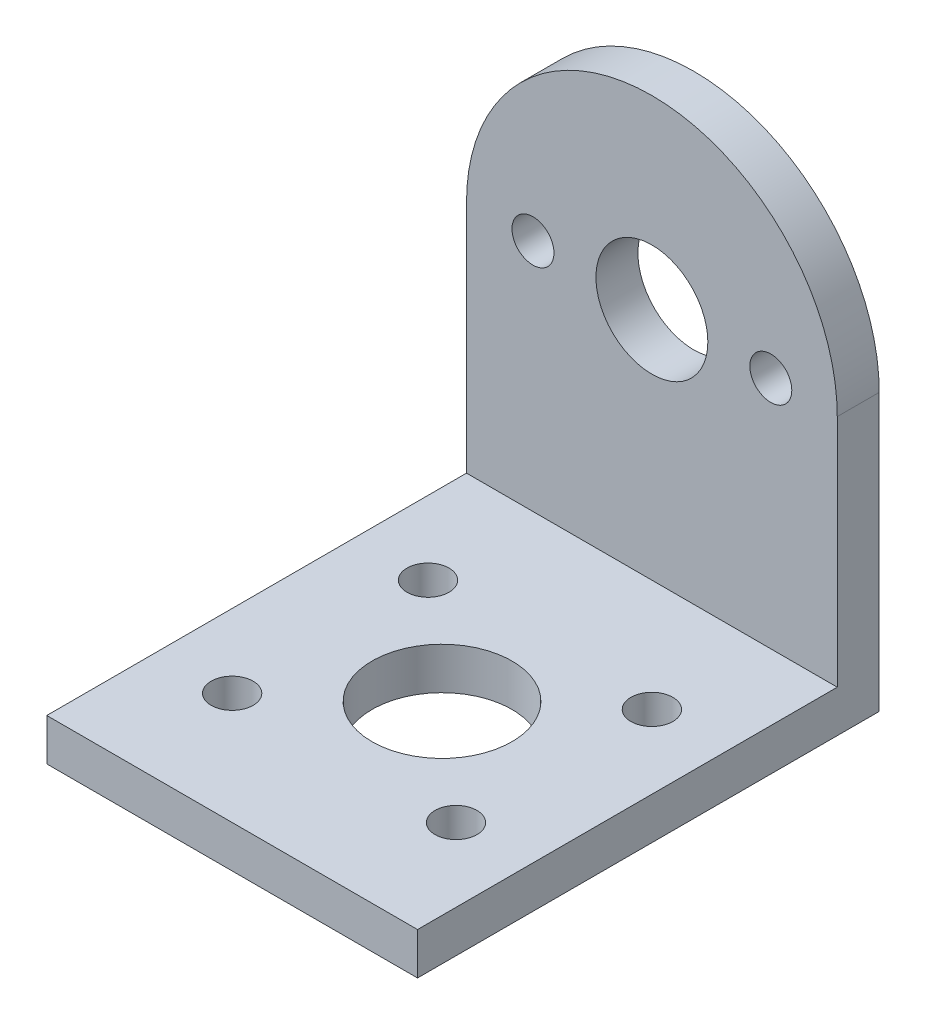
SolidWorks part; units mm, degrees
ref_plane "前视基准面" through (0, 0, 0) normal (0, 0, 1) x (1, 0, 0)
ref_plane "上视基准面" through (0, 0, 0) normal (0, 1, 0) x (1, 0, 0)
ref_plane "右视基准面" through (0, 0, 0) normal (1, 0, 0) x (0, 0, -1)
sketch "草图1" plane through (0, 0, 0) normal (0, 1, 0) x (1, 0, 0)
  line L0 (0, 46.5385) -> (0, -55) construction
  line L1 (-17.8515, -18) -> (21.8548, -18) construction
  line L2 (-13.25, 0) -> (13.25, 0)
  line L3 (-13.25, 0) -> (-13.25, -33)
  line L4 (-13.25, -33) -> (13.25, -33)
  line L5 (13.25, 0) -> (13.25, -33)
  circle A0 centre (0, -18) radius 5
  circle A1 centre (-8, -11) radius 1.5
  circle A2 centre (8, -11) radius 1.5
  circle A3 centre (-8, -25) radius 1.5
  circle A4 centre (8, -25) radius 1.5
  dimension "D3" = 10
  dimension "D5" = 3
  dimension "D6" = 3
  dimension "D7" = 3
  dimension "D8" = 3
  dimension "D1" = 33
  dimension "D2" = 26.5
  dimension "D4" = 15
  dimension "D9" = 14
  dimension "D10" = 16
  dimension "D11" = 18
extrude "凸台-拉伸1" add sketch "草图1" along normal blind 3
sketch "草图2" plane through (0, 0, 0) normal (0, 0, 1) x (1, 0, 0)
  line L0 (-13.25, 3) -> (-13.25, 19.75)
  line L1 (13.25, 3) -> (13.25, 19.75)
  line L2 (-13.25, 19.75) -> (13.25, 19.75) construction
  line L3 (0, 33) -> (0, 0) construction
  line L5 (-13.25, 3) -> (13.25, 3)
  arc A0 (-13.25, 19.75) -> (13.25, 19.75) centre (0, 19.75) cw
  circle A1 centre (0, 19.75) radius 4
  circle A2 centre (-8.5, 19.75) radius 1.5
  circle A3 centre (8.5, 19.75) radius 1.5
  dimension "D1" = 33
  dimension "D2" = 8
  dimension "D3" = 3
  dimension "D4" = 3
  dimension "D5" = 17
extrude "凸台-拉伸2" add sketch "草图2" along normal blind 3
